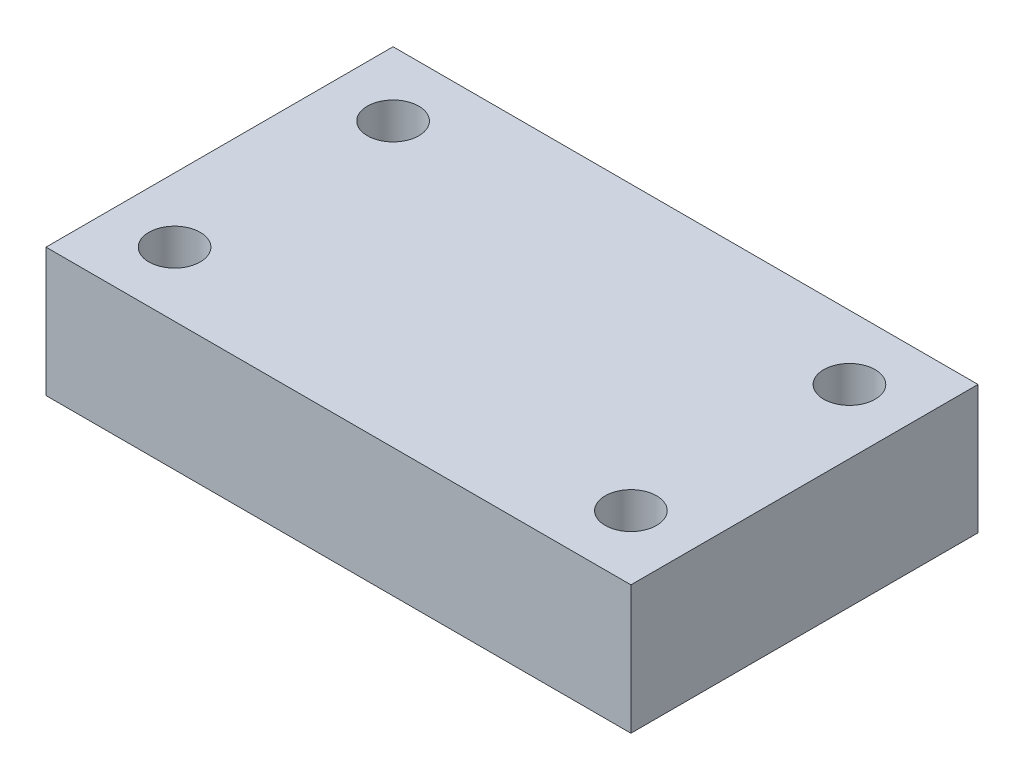
SolidWorks part; units mm, degrees
ref_plane "Front Plane" through (0, 0, 0) normal (0, 0, 1) x (1, 0, 0)
ref_plane "Top Plane" through (0, 0, 0) normal (0, 1, 0) x (1, 0, 0)
ref_plane "Right Plane" through (0, 0, 0) normal (1, 0, 0) x (0, 0, -1)
sketch "Sketch1" plane through (0, 0, 0) normal (0, 1, 0) x (1, 0, 0)
  line L0 (-22.75, 13.5) -> (22.75, 13.5)
  line L1 (-22.75, 13.5) -> (-22.75, -13.5)
  line L2 (-22.75, -13.5) -> (22.75, -13.5)
  line L3 (22.75, 13.5) -> (22.75, -13.5)
  line L4 (22.75, 13.5) -> (16.5851, 13.5)
  line L5 (-17.75, 8.5) -> (-17.75, -8.5) construction
  line L6 (-17.75, -8.5) -> (17.75, -8.5) construction
  line L7 (17.75, -8.5) -> (17.75, 8.5) construction
  line L8 (17.75, 8.5) -> (-17.75, 8.5) construction
  line L9 (0, 13.5) -> (0, -13.5) construction
  line L10 (-22.75, 0) -> (22.75, 0) construction
  circle A0 centre (-17.75, 8.5) radius 2
  circle A1 centre (-17.75, -8.5) radius 2
  circle A2 centre (17.75, 8.5) radius 2
  circle A3 centre (17.75, -8.5) radius 2
  point P13 (-22.75, 13.5)
  point P18 (0, 0)
  dimension "D3" = 4
  dimension "D5" = 4
  dimension "D6" = 4
  dimension "D7" = 4
  dimension "D1" = 45.5
  dimension "D2" = 27
  dimension "D4" = 17
  dimension "D8" = 35.5
  dimension "D9" = 5
  dimension "D10" = 5
extrude "Boss-Extrude1" add sketch "Sketch1" along normal blind 10 contours L3 L2 L1 L0 | A1 | A0 | A3 | A2
sketch "Sketch2" plane through (0, 0, 0) normal (0, -1, 0) x (1, 0, 0)
  line L0 (0, 13.5) -> (0, -13.5) construction
  line L1 (-22.75, 13.5) -> (22.75, 13.5) construction
  line L2 (-22.75, -13.5) -> (22.75, -13.5) construction
  circle A0 centre (-17.75, 8.5) radius 3
  circle A1 centre (-17.75, -8.5) radius 3
  circle A2 centre (17.75, -8.5) radius 3
  circle A3 centre (17.75, 8.5) radius 3
  dimension "D1" = 6
  dimension "D2" = 6
extrude "Cut-Extrude1" cut sketch "Sketch2" against normal blind 6
